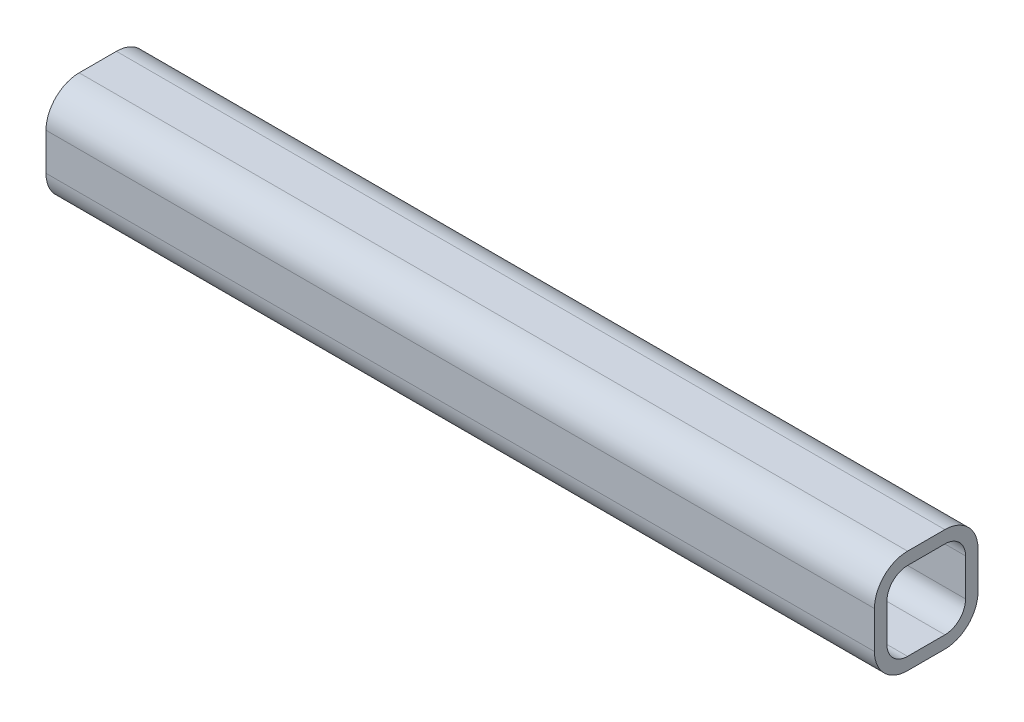
SolidWorks part; units mm, degrees
material "5052-H38, Rod (SS)"
ref_plane "Front Plane" through (0, 0, 0) normal (0, 0, 1) x (1, 0, 0)
ref_plane "Top Plane" through (0, 0, 0) normal (0, 1, 0) x (1, 0, 0)
ref_plane "Right Plane" through (0, 0, 0) normal (1, 0, 0) x (0, 0, -1)
sketch "Sketch2" plane through (0, 0, 0) normal (1, 0, 0) x (0, 0, -1)
  line L1 (-4.5, -9.5) -> (4.5, -9.5)
  line L2 (-9.5, -4.5) -> (-9.5, 4.5)
  line L3 (-4.5, 9.5) -> (4.5, 9.5)
  line L4 (9.5, -4.5) -> (9.5, 4.5)
  line L5 (-9.5, -9.5) -> (9.5, 9.5) construction
  line L6 (-9.5, 9.5) -> (9.5, -9.5) construction
  arc A0 (-4.5, 9.5) -> (-9.5, 4.5) centre (-4.5, 4.5) ccw
  arc A1 (-9.5, -4.5) -> (-4.5, -9.5) centre (-4.5, -4.5) ccw
  arc A2 (4.5, -9.5) -> (9.5, -4.5) centre (4.5, -4.5) ccw
  arc A3 (9.5, 4.5) -> (4.5, 9.5) centre (4.5, 4.5) ccw
  point P0 (0, 0)
  dimension "D3" = 5
  dimension "D1" = 19
  dimension "D2" = 19
sketch "Sketch3" plane through (0, 0, 0) normal (0, 1, 0) x (1, 0, 0)
  line L0 (0, 0) -> (200, 0)
  dimension "D1" = 200
sweep "Sweep-Thin1" add profiles "Sketch2" path "Sketch3" parameters "D1"=3
